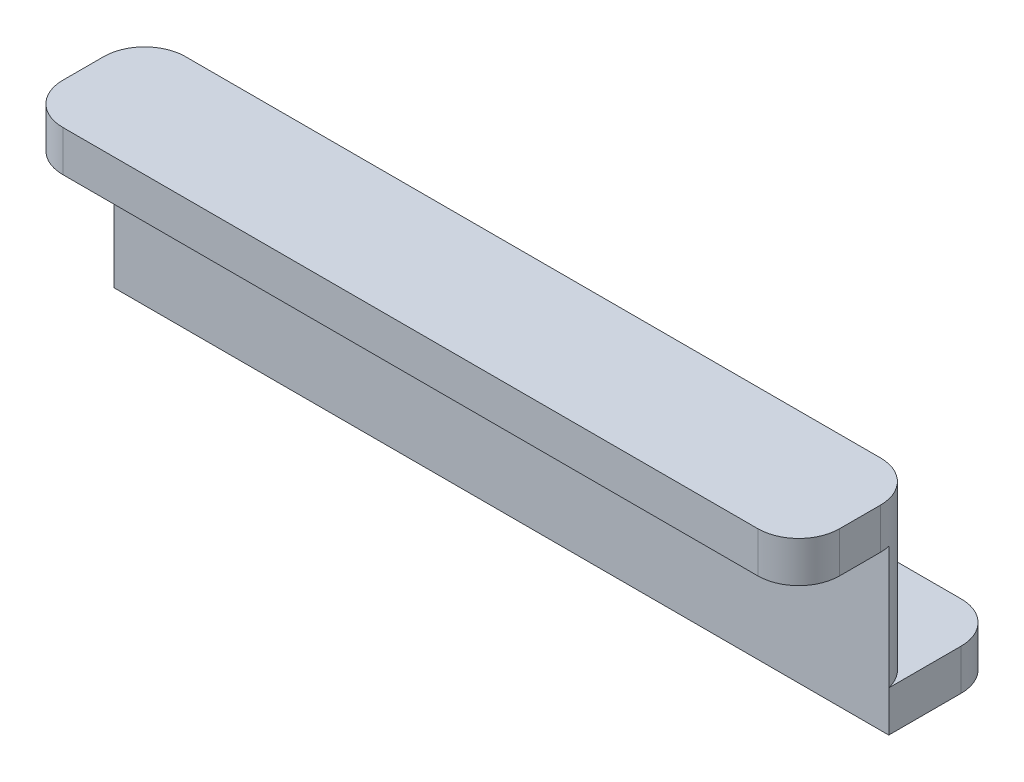
SolidWorks part; units mm, degrees
ref_plane "Front Plane" through (0, 0, 0) normal (0, 0, 1) x (1, 0, 0)
ref_plane "Top Plane" through (0, 0, 0) normal (0, 1, 0) x (1, 0, 0)
ref_plane "Right Plane" through (0, 0, 0) normal (1, 0, 0) x (0, 0, -1)
sketch "Sketch1" plane through (0, 0, 0) normal (0, 1, 0) x (1, 0, 0)
  line L0 (0, -3) -> (0, 3) construction
  line L1 (-17, -3) -> (17, -3)
  line L2 (-19, -1) -> (-19, 1)
  line L3 (-17, 3) -> (17, 3)
  line L4 (19, -1) -> (19, 1)
  arc A0 (17, 3) -> (19, 1) centre (17, 1) cw
  arc A1 (17, -3) -> (19, -1) centre (17, -1) ccw
  arc A2 (-17, -3) -> (-19, -1) centre (-17, -1) cw
  arc A3 (-19, 1) -> (-17, 3) centre (-17, 1) cw
  point P11 (0, 0)
  point P20 (0, 0)
  dimension "D1" = 2
  dimension "D2" = 2
  dimension "D3" = 38
  dimension "D4" = 6
extrude "Boss-Extrude1" add sketch "Sketch1" along normal blind 2
sketch "Sketch2" plane through (0, 2, 0) normal (0, 1, 0) x (1, 0, 0)
  line L0 (0, -3) -> (0, 10.7795) construction
  line L1 (-17, -3) -> (17, -3) construction
  line L5 (17, 3) -> (-17, 3) construction
  line L6 (17, 3) -> (-17, 3)
  line L7 (18.9469, 1.4578) -> (-18.9469, 1.4578)
  arc A5 (-17, 3) -> (-19, 1) centre (-17, 1) ccw construction
  arc A6 (19, 1) -> (17, 3) centre (17, 1) ccw construction
  arc A9 (-17, 3) -> (-18.9469, 1.4578) centre (-17, 1) ccw
  arc A10 (18.9469, 1.4578) -> (17, 3) centre (17, 1) ccw
  dimension "D1" = 1.5422
extrude "Boss-Extrude2" add sketch "Sketch2" against normal blind 10
sketch "Sketch4" plane through (0, -8, 0) normal (0, -1, 0) x (1, 0, 0)
  line L3 (17, -3) -> (-17, -3) construction
  line L5 (-18.9469, -1.4578) -> (-18.9469, -5)
  line L6 (18.9469, -1.4578) -> (-18.9469, -1.4578) construction
  line L11 (17, -3) -> (-17, -3)
  line L12 (18.9469, -1.4578) -> (-18.9469, -1.4578) construction
  line L13 (-16.9469, -7) -> (16.9469, -7)
  line L14 (18.9469, -5) -> (18.9469, -1.4578)
  arc A0 (-19, -1) -> (-17, -3) centre (-17, -1) ccw construction
  arc A1 (17, -3) -> (19, -1) centre (17, -1) ccw construction
  arc A8 (-18.9469, -1.4578) -> (-17, -3) centre (-17, -1) ccw
  arc A9 (-18.9469, -5) -> (-16.9469, -7) centre (-16.9469, -5) ccw
  arc A10 (16.9469, -7) -> (18.9469, -5) centre (16.9469, -5) ccw
  arc A14 (17, -3) -> (18.9469, -1.4578) centre (17, -1) ccw
  dimension "D1" = 2
  dimension "D2" = 4
extrude "Boss-Extrude3" add sketch "Sketch4" against normal blind 2
sketch "Sketch5" [suppressed] plane through (0, 2, 0) normal (0, 1, 0) x (1, 0, 0)
  line L0 (19, 1) -> (19, 12.07)
  line L1 (16.1, 14.97) -> (-16.1, 14.97)
  line L2 (-19, 12.07) -> (-19, 1)
  line L3 (-19, 1) -> (-16.1, 3)
  line L4 (-16.1, 3) -> (16.1, 3)
  line L5 (16.1, 3) -> (19, 1)
  line L6 (-17, -3) -> (17, -3) construction
  line L8 (17, 3) -> (-17, 3) construction
  arc A0 (-16.1, 14.97) -> (-19, 12.07) centre (-16.1, 12.07) ccw
  arc A1 (19, 12.07) -> (16.1, 14.97) centre (16.1, 12.07) ccw
  dimension "D1" = 2.9
  dimension "D2" = 17.97
extrude "Boss-Extrude4" [suppressed] add sketch "Sketch5" against normal up to surface (2 mm away)
sketch "Sketch6" [suppressed] plane through (0, 0, 0) normal (0, -1, 0) x (1, 0, 0)
  line L0 (16.1, -14.97) -> (-16.1, -14.97) construction
  line L1 (19, -5.535) -> (-19, -5.535) construction
  line L2 (19, 1) -> (19, -12.07) construction
  line L4 (-19, -12.07) -> (-19, 1) construction
  line L5 (-35.6, -3.0737) -> (-35.6, 0.4819) construction
  line L8 (19, -1.4578) -> (-19, -1.4578)
  line L12 (-17, -3) -> (17, -3) construction
  line L16 (0, 3) -> (0, -14.97) construction
  line L17 (-17, 3) -> (17, 3) construction
  line L18 (35.6, -3.0737) -> (35.6, 0.4819) construction
  line L21 (35.5, 0.3551) -> (35.5, -0.9477) construction
  line L22 (19, -1.4578) -> (19, -9.6122)
  line L23 (19, -9.6122) -> (-19, -9.6122)
  line L24 (-19, -1.4578) -> (-19, -9.6122)
  line L25 (19, 1) -> (19, -12.07) construction
  line L26 (-18.9469, -1.4578) -> (18.9469, -1.4578) construction
  dimension "D1" = 0.1
extrude "Boss-Extrude5" [suppressed] add sketch "Sketch6" along normal up to surface (8 mm away)
